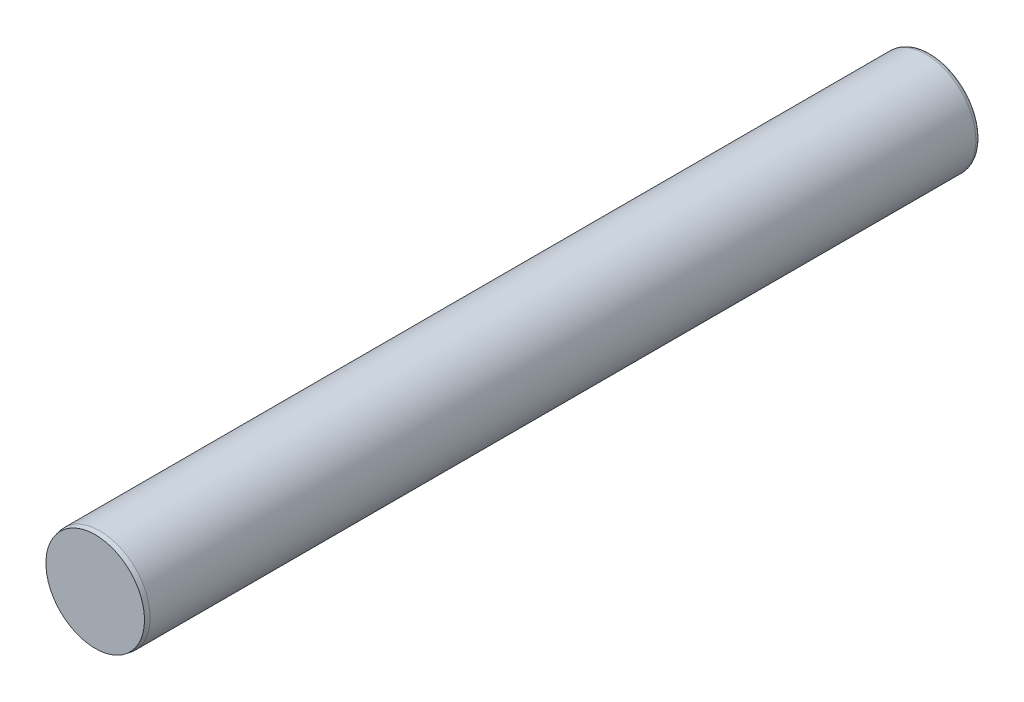
SolidWorks part; units mm, degrees
material "Plain Carbon Steel"
ref_plane "Front Plane" through (0, 0, 0) normal (0, 0, 1) x (1, 0, 0)
ref_plane "Top Plane" through (0, 0, 0) normal (0, 1, 0) x (1, 0, 0)
ref_plane "Right Plane" through (0, 0, 0) normal (1, 0, 0) x (0, 0, -1)
sketch "Sketch1" plane through (0, 0, 0) normal (1, 0, 0) x (0, 0, -1)
  line L0 (0, 0) -> (99.9337, 0) construction
  line L1 (0, 0) -> (0, 5.9)
  line L2 (0, 5.9) -> (0.5671, 6)
  line L3 (0.5671, 6) -> (99.4, 6)
  line L4 (100, 5.4) -> (100, 0)
  line L5 (0, 0) -> (100, 0)
  arc A0 (100, 5.4) -> (99.4, 6) centre (99.4, 5.4) ccw
  dimension "D4" = 0.6
  dimension "D1" = 12
  dimension "D2" = 11.8
  dimension "D3" = 10
  dimension "D5" = 100
revolve "Revolve1" add sketch "Sketch1" angle 360 about L0
